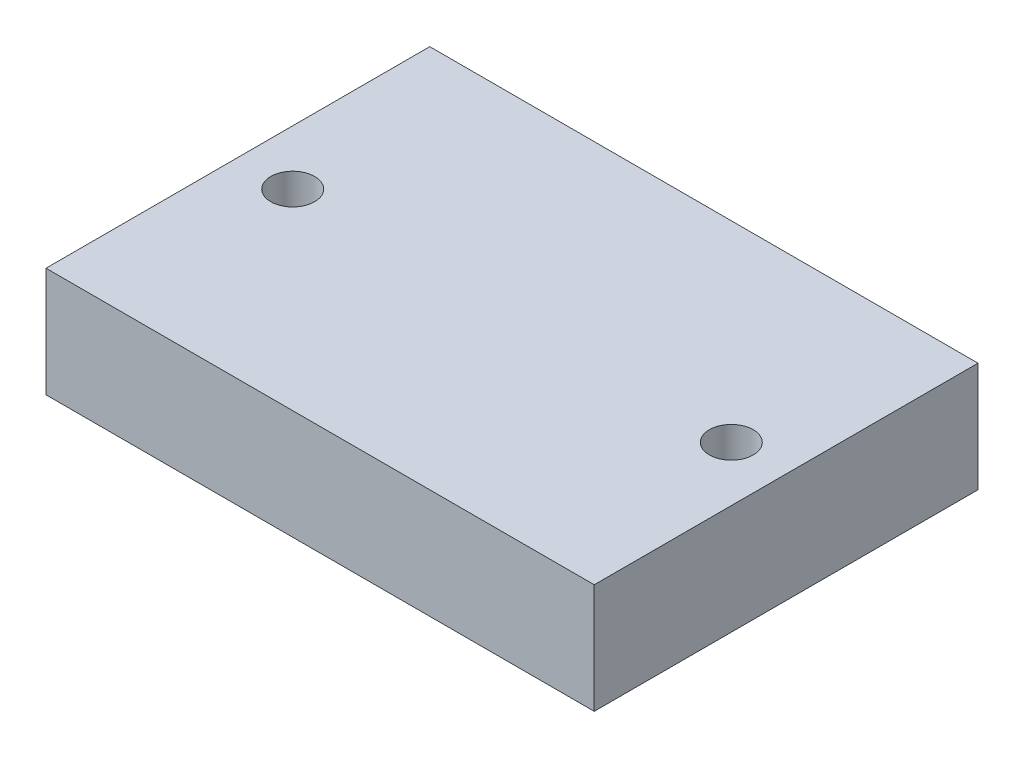
SolidWorks part; units mm, degrees
ref_plane "Front Plane" through (0, 0, 0) normal (0, 0, 1) x (1, 0, 0)
ref_plane "Top Plane" through (0, 0, 0) normal (0, 1, 0) x (1, 0, 0)
ref_plane "Right Plane" through (0, 0, 0) normal (1, 0, 0) x (0, 0, -1)
sketch "Sketch1" plane through (0, 0, 0) normal (0, 1, 0) x (1, 0, 0)
  line L1 (-25, 17.5) -> (25, 17.5)
  line L2 (-25, 17.5) -> (-25, -17.5)
  line L3 (-25, -17.5) -> (25, -17.5)
  line L4 (25, 17.5) -> (25, -17.5)
  line L5 (-25, 17.5) -> (25, -17.5) construction
  line L6 (-25, -17.5) -> (25, 17.5) construction
  point P0 (0, 0)
  dimension "D1" = 50
  dimension "D2" = 35
extrude "Boss-Extrude1" add sketch "Sketch1" along normal blind 10
sketch "Sketch2" plane through (0, 10, 0) normal (0, 1, 0) x (1, 0, 0)
  line L0 (0, -5.5) -> (0, 5.5) construction
  point P0 (-20, 0)
  point P4 (20, 0)
  dimension "D1" = 20
hole_wizard "Ø4.0mm Dowel Hole1" positions "Sketch2" profile "Sketch3" hole size "Ø4.0" standard "ISO" end condition through all
sketch "Sketch3" plane through (-20, 10, 0) normal (1, 0, 0) x (0, 0, 1)
  line L0 (0, 0) -> (0, 10)
  line L1 (0, 10) -> (2, 10)
  line L2 (2, 10) -> (2, 0)
  line L5 (2, 0) -> (0, 0)
  line L11 (0, -6.35) -> (0, 107.95) construction
  dimension "Thru Hole Dia." = 4
  dimension "Thru Hole Depth" = 10
